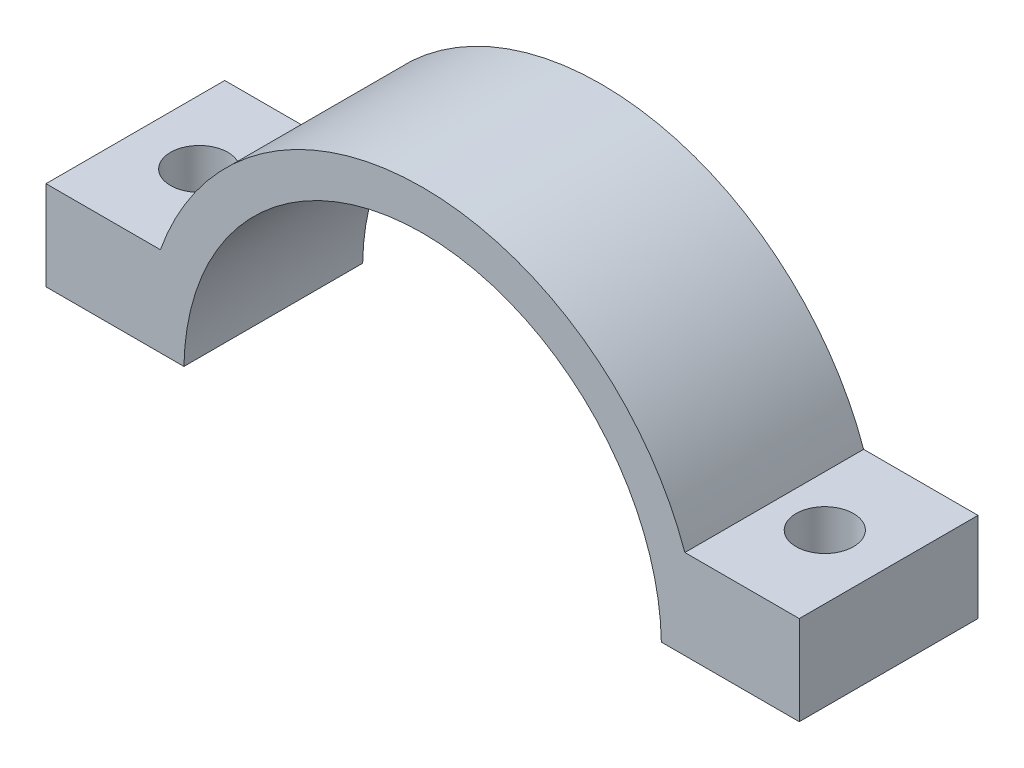
SolidWorks part; units mm, degrees
ref_plane "Front Plane" through (0, 0, 0) normal (0, 0, 1) x (1, 0, 0)
ref_plane "Top Plane" through (0, 0, 0) normal (0, 1, 0) x (1, 0, 0)
ref_plane "Right Plane" through (0, 0, 0) normal (1, 0, 0) x (0, 0, -1)
sketch "Bolted cap and ears profile" plane through (0, 0, 0) normal (0, 0, 1) x (1, 0, 0)
  line L0 (20.5414, 35.8) -> (29.5, 35.8)
  line L1 (29.5, 35.8) -> (29.5, 28.8)
  line L2 (29.5, 28.8) -> (18.6976, 28.8)
  line L3 (-18.6976, 28.8) -> (-29.5, 28.8)
  line L4 (-29.5, 28.8) -> (-29.5, 35.8)
  line L5 (-29.5, 35.8) -> (-20.5414, 35.8)
  arc A0 (-20.5414, 35.8) -> (20.5414, 35.8) centre (0, 28.5) cw
  arc A1 (18.6976, 28.8) -> (-18.6976, 28.8) centre (0, 28.5) ccw
extrude "Bolted cap and ears" add sketch "Bolted cap and ears profile" along normal blind 14
sketch "Sketch2" plane through (0, 0, 0) normal (0, 1, 0) x (1, 0, 0)
  circle A0 centre (-24.5, -7) radius 2.25
  circle A1 centre (24.5, -7) radius 2.25
extrude "M4 through holes" cut sketch "Sketch2" against normal through all and the other way through all
